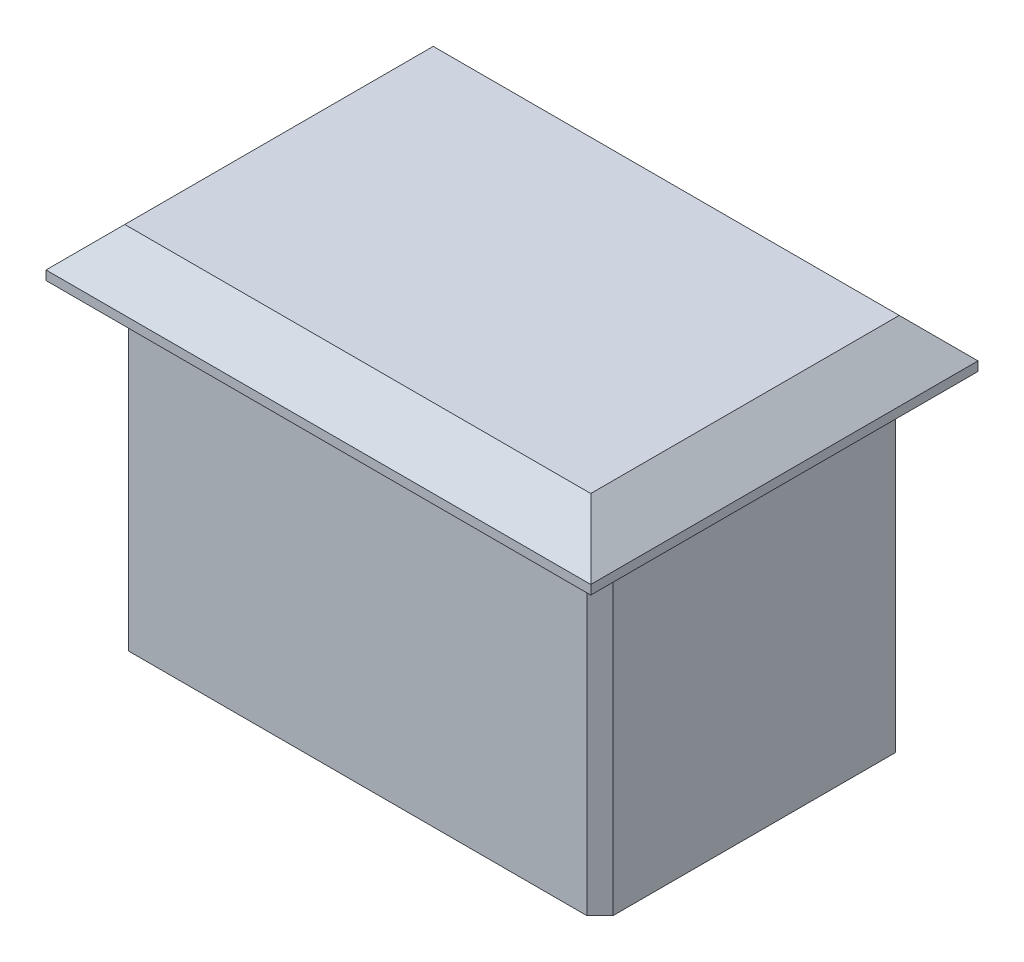
SolidWorks part; units mm, degrees
material "PBT General Purpose"
ref_plane "Front Plane" through (0, 0, 0) normal (0, 0, 1) x (1, 0, 0)
ref_plane "Top Plane" through (0, 0, 0) normal (0, 1, 0) x (1, 0, 0)
ref_plane "Right Plane" through (0, 0, 0) normal (1, 0, 0) x (0, 0, -1)
sketch "Sketch1" plane through (0, 0, 0) normal (0, 1, 0) x (1, 0, 0)
  line L1 (9.225, 5.875) -> (-9.225, 5.875)
  line L2 (9.225, 5.875) -> (9.225, -5.875)
  line L3 (9.225, -5.875) -> (-9.225, -5.875)
  line L4 (-9.225, 5.875) -> (-9.225, -5.875)
  line L5 (9.225, 5.875) -> (-9.225, -5.875) construction
  line L6 (9.225, -5.875) -> (-9.225, 5.875) construction
  point P0 (0, 0)
  dimension "D1" = 11.75
  dimension "D2" = 18.45
extrude "Boss-Extrude1" add sketch "Sketch1" along normal blind 14
sketch "Sketch2" plane through (0, 14, 0) normal (0, 1, 0) x (1, 0, 0)
  line L1 (10.375, 7.375) -> (-10.375, 7.375)
  line L2 (10.375, 7.375) -> (10.375, -7.375)
  line L3 (10.375, -7.375) -> (-10.375, -7.375)
  line L4 (-10.375, 7.375) -> (-10.375, -7.375)
  line L5 (10.375, 7.375) -> (-10.375, -7.375) construction
  line L6 (10.375, -7.375) -> (-10.375, 7.375) construction
  point P0 (0, 0)
  dimension "D1" = 14.75
  dimension "D2" = 20.75
extrude "Boss-Extrude2" add sketch "Sketch2" against normal blind 1.85
chamfer "Chamfer1" distance 1.5 angle 45 4 edges at (0, 14, -7.375) (10.375, 14, 0) (0, 14, 7.375) (-10.375, 14, 0)
chamfer "Chamfer2" distance 0.5 angle 45 4 edges at (9.225, 6.075, -5.875) (9.225, 6.075, 5.875) (-9.225, 6.075, -5.875) (-9.225, 6.075, 5.875)
